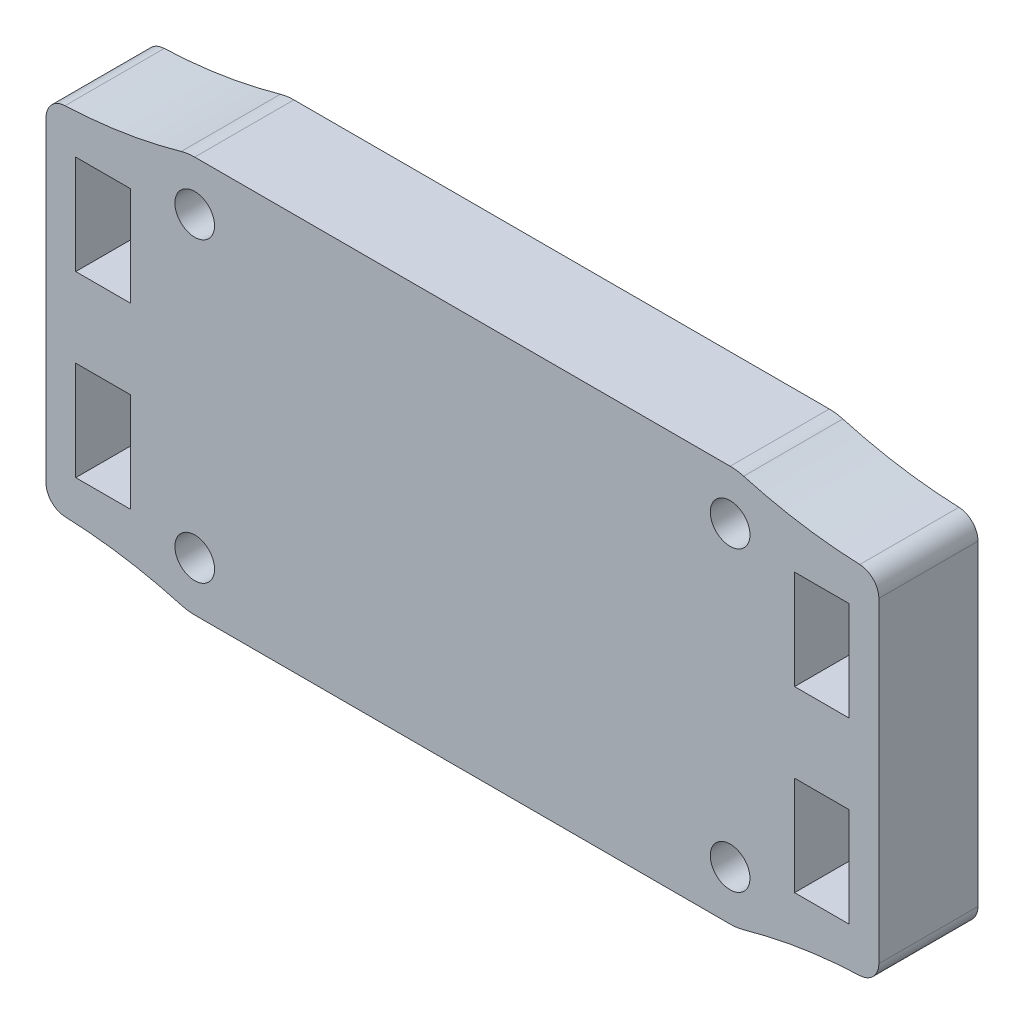
SolidWorks part; units mm, degrees
ref_plane "Plan de face" through (0, 0, 0) normal (0, 0, 1) x (1, 0, 0)
ref_plane "Plan de dessus" through (0, 0, 0) normal (0, 1, 0) x (1, 0, 0)
ref_plane "Plan de droite" through (0, 0, 0) normal (1, 0, 0) x (0, 0, -1)
sketch "Esquisse1" plane through (0, 0, 0) normal (0, 0, 1) x (1, 0, 0)
  line L0 (9.2759, -0.1216) -> (9.2759, -8.3527) construction
  line L4 (22.7759, -16.4263) -> (-4.2241, -16.4263)
  line L5 (30.2759, -14.403) -> (30.2759, 1.5505)
  line L6 (22.7759, 3.5737) -> (-4.2241, 3.5737)
  line L7 (-11.7241, -14.403) -> (-11.7241, 1.5505)
  line L8 (28.7759, -8.4263) -> (28.7759, -13.4263)
  line L9 (-10.2241, 0.5737) -> (-7.4741, 0.5737)
  line L11 (-10.2241, 0.5737) -> (-10.2241, -4.4263)
  line L13 (-7.4741, 0.5737) -> (-7.4741, -4.4263)
  line L14 (-10.2241, -13.4263) -> (-7.4741, -13.4263)
  line L15 (-10.2241, -8.4263) -> (-7.4741, -8.4263)
  line L16 (-10.2241, -4.4263) -> (-7.4741, -4.4263)
  line L18 (-6.7241, -6.4263) -> (25.2759, -6.4263) construction
  line L19 (-7.4741, -8.4263) -> (-7.4741, -13.4263)
  line L20 (-10.2241, -8.4263) -> (-10.2241, -13.4263)
  line L21 (28.7759, -13.4263) -> (26.0259, -13.4263)
  line L22 (26.0259, -8.4263) -> (26.0259, -13.4263)
  line L23 (28.7759, -8.4263) -> (26.0259, -8.4263)
  line L24 (26.0259, 0.5737) -> (26.0259, -4.4263)
  line L25 (28.7759, -4.4263) -> (26.0259, -4.4263)
  line L26 (28.7759, 0.5737) -> (28.7759, -4.4263)
  line L27 (28.7759, 0.5737) -> (26.0259, 0.5737)
  arc A4 (-4.2241, 3.5737) -> (-4.906, 3.479) centre (-4.2241, 1.0737) ccw
  circle A6 centre (-4.2241, 1.0737) radius 1
  circle A7 centre (22.7759, 1.0737) radius 1
  circle A8 centre (22.7759, -13.9263) radius 1
  circle A10 centre (-4.2241, -13.9263) radius 1
  arc A12 (-10.7626, 2.5497) -> (-4.906, 3.479) centre (-11.7241, 27.5313) ccw
  arc A13 (-10.7626, 2.5497) -> (-11.7241, 1.5505) centre (-10.7241, 1.5505) ccw
  arc A14 (-10.7626, -15.4023) -> (-11.7241, -14.403) centre (-10.7241, -14.403) cw
  arc A15 (-10.7626, -15.4023) -> (-4.906, -16.3315) centre (-11.7241, -40.3838) cw
  arc A16 (-4.2241, -16.4263) -> (-4.906, -16.3315) centre (-4.2241, -13.9263) cw
  arc A17 (29.3143, -15.4023) -> (30.2759, -14.403) centre (29.2759, -14.403) ccw
  arc A18 (29.3143, -15.4023) -> (23.4577, -16.3315) centre (30.2759, -40.3838) ccw
  arc A19 (22.7759, -16.4263) -> (23.4577, -16.3315) centre (22.7759, -13.9263) ccw
  arc A20 (29.3143, 2.5497) -> (30.2759, 1.5505) centre (29.2759, 1.5505) cw
  arc A21 (22.7759, 3.5737) -> (23.4577, 3.479) centre (22.7759, 1.0737) cw
  arc A22 (29.3143, 2.5497) -> (23.4577, 3.479) centre (30.2759, 27.5313) cw
  dimension "D7" = 2
  dimension "D8" = 5
  dimension "D10" = 2
  dimension "D11" = 2
  dimension "D12" = 1.5
  dimension "D3" = 13.5
  dimension "D4" = 50
  dimension "D16" = 5
  dimension "D17" = 5
  dimension "D18" = 3
  dimension "D19" = 3
extrude "Boss.-Extru.1" add sketch "Esquisse1" along normal blind 5
